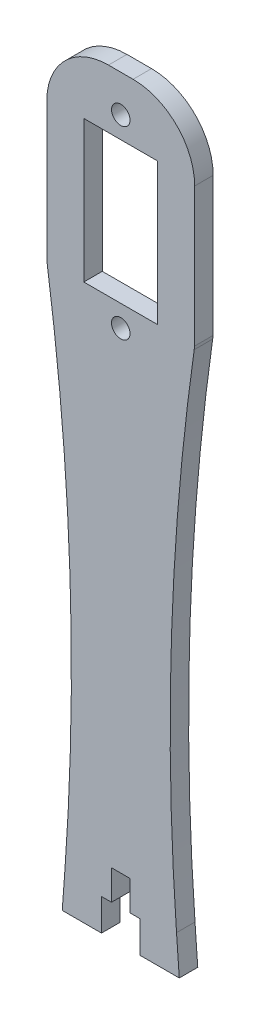
SolidWorks part; units mm, degrees
material "Pinho"
ref_plane "Plano frontal" through (0, 0, 0) normal (0, 0, 1) x (1, 0, 0)
ref_plane "Plano superior" through (0, 0, 0) normal (0, 1, 0) x (1, 0, 0)
ref_plane "Plano direito" through (0, 0, 0) normal (1, 0, 0) x (0, 0, -1)
sketch "Esboço1" plane through (0, 0, 0) normal (0, 0, 1) x (1, 0, 0)
  line L0 (3.125, -119.95) -> (3.125, -125.1)
  line L1 (0, -2.5) -> (2, -2.5)
  line L2 (3.125, -119.95) -> (1.5, -119.95)
  line L3 (-3.125, -119.95) -> (-3.125, -125.1)
  line L4 (-2, -2.5) -> (0, -2.5)
  line L5 (9.5, -125.1) -> (3.125, -125.1)
  line L6 (-1.5, -119.95) -> (-3.125, -119.95)
  line L7 (9.5, -125.1) -> (9.0514, -118.9484)
  line L8 (-12, -35) -> (-11.9202, -35.5603)
  line L9 (-9.5, -125.1) -> (-9.0514, -118.9484)
  line L10 (12, -35) -> (11.9202, -35.5603)
  line L12 (-1.5, -119.95) -> (-1.5, -115.1)
  line L13 (-1.5, -115.1) -> (1.5, -115.1)
  line L14 (12, -35) -> (12, -12.5)
  line L15 (1.5, -115.1) -> (1.5, -119.95)
  line L16 (-3.125, -125.1) -> (-9.5, -125.1)
  line L18 (-6, -23.5) -> (-6, -12)
  line L19 (-6, -23.5) -> (-6, -35)
  line L20 (6, -35) -> (6, -12)
  line L21 (-12, -35) -> (-12, -12.5)
  line L22 (-6, -35) -> (-2.5, -35)
  line L23 (6, -35) -> (2.4747, -35)
  line L24 (6, -12) -> (-6, -12)
  line L25 (2.4747, -35) -> (-2.5, -35)
  arc A0 (12, -12.5) -> (2, -2.5) centre (2, -12.5) ccw
  circle A1 centre (0, -8.5) radius 1.5
  arc A2 (9.0514, -118.9484) -> (11.9202, -35.5603) centre (398.0188, -90.5862) cw
  arc A3 (-9.0514, -118.9484) -> (-11.9202, -35.5603) centre (-398.0188, -90.5862) ccw
  arc A4 (-12, -12.5) -> (-2, -2.5) centre (-2, -12.5) cw
  circle A5 centre (0, -38.4999) radius 1.5
extrude "Ressalto-extrusão1" add sketch "Esboço1" along normal blind 3
